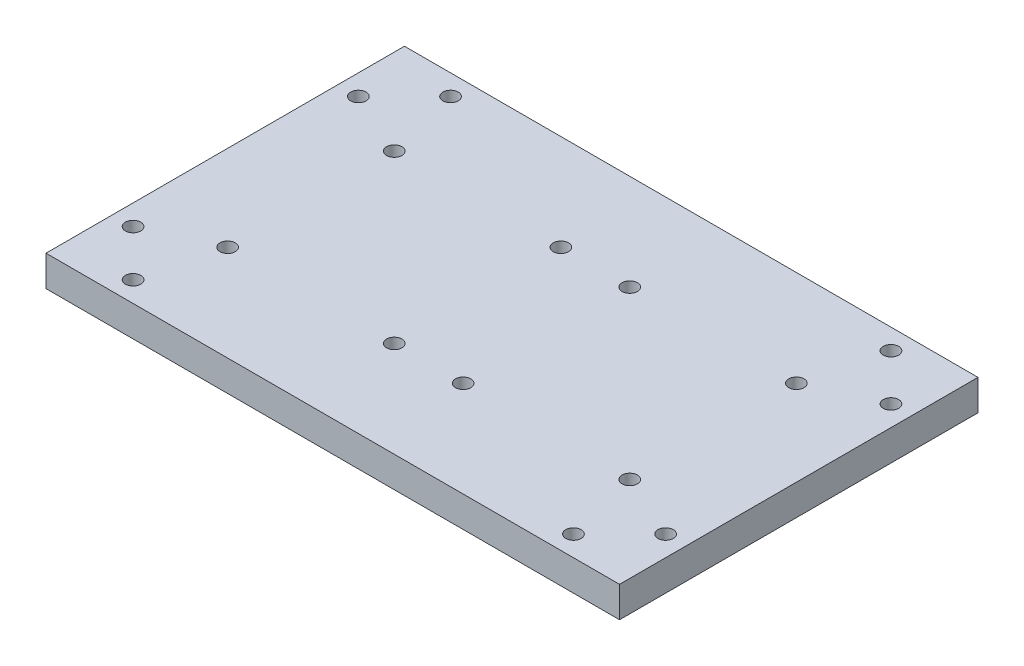
SolidWorks part; units mm, degrees
ref_plane "Front Plane" through (0, 0, 0) normal (0, 0, 1) x (1, 0, 0)
ref_plane "Top Plane" through (0, 0, 0) normal (0, 1, 0) x (1, 0, 0)
ref_plane "Right Plane" through (0, 0, 0) normal (1, 0, 0) x (0, 0, -1)
sketch "Sketch1" plane through (0, 0, 0) normal (0, 1, 0) x (1, 0, 0)
  line L1 (0, 0) -> (112, 0)
  line L2 (0, 0) -> (0, 70)
  line L3 (0, 70) -> (112, 70)
  line L4 (112, 0) -> (112, 70)
  dimension "D1" = 70
  dimension "D2" = 112
extrude "Boss-Extrude1" add sketch "Sketch1" along normal blind 6
sketch "Sketch2" plane through (0, 6, 0) normal (0, 1, 0) x (1, 0, 0)
  line L0 (56, 0) -> (56, 70) construction
  line L1 (0, 0) -> (112, 0) construction
  line L2 (112, 70) -> (0, 70) construction
  line L3 (62.735, 51.265) -> (95.265, 51.265) construction
  line L4 (79, 51.265) -> (79, 27.0502) construction
  circle A0 centre (62.735, 51.265) radius 1.5
  circle A1 centre (95.265, 51.265) radius 1.5
  circle A2 centre (62.735, 18.735) radius 1.5
  circle A3 centre (95.265, 18.735) radius 1.5
  circle A4 centre (16.735, 18.735) radius 1.5
  circle A5 centre (16.735, 51.265) radius 1.5
  circle A6 centre (49.265, 51.265) radius 1.5
  circle A7 centre (49.265, 18.735) radius 1.5
  point P14 (56, 35)
  dimension "D1" = 3
  dimension "D2" = 3
  dimension "D3" = 3
  dimension "D4" = 3
  dimension "D5" = 32.53
  dimension "D6" = 32.53
  dimension "D7" = 32.53
  dimension "D8" = 32.53
  dimension "D9" = 16.265
  dimension "D10" = 23
  dimension "D11" = 0
extrude "Cut-Extrude1" cut sketch "Sketch2" against normal blind 6
sketch "Sketch3" plane through (0, 6, 0) normal (0, 1, 0) x (1, 0, 0)
  line L0 (56, 0) -> (56, 70) construction
  line L1 (0, 0) -> (112, 0) construction
  line L2 (112, 70) -> (0, 70) construction
  line L3 (0, 35) -> (112, 35) construction
  line L4 (0, 70) -> (0, 0) construction
  line L5 (112, 0) -> (112, 70) construction
  circle A0 centre (4, 57) radius 1.5
  circle A1 centre (13, 66) radius 1.5
  circle A2 centre (99, 66) radius 1.5
  circle A3 centre (108, 57) radius 1.5
  circle A4 centre (108, 13) radius 1.5
  circle A5 centre (99, 4) radius 1.5
  circle A6 centre (13, 4) radius 1.5
  circle A7 centre (4, 13) radius 1.5
  point P16 (0, 0)
  point P18 (12.8949, 69.0142)
  dimension "D1" = 3
  dimension "D2" = 3
  dimension "D3" = 13
  dimension "D4" = 13
  dimension "D5" = 4
  dimension "D6" = 4
extrude "Cut-Extrude2" cut sketch "Sketch3" against normal blind 10
